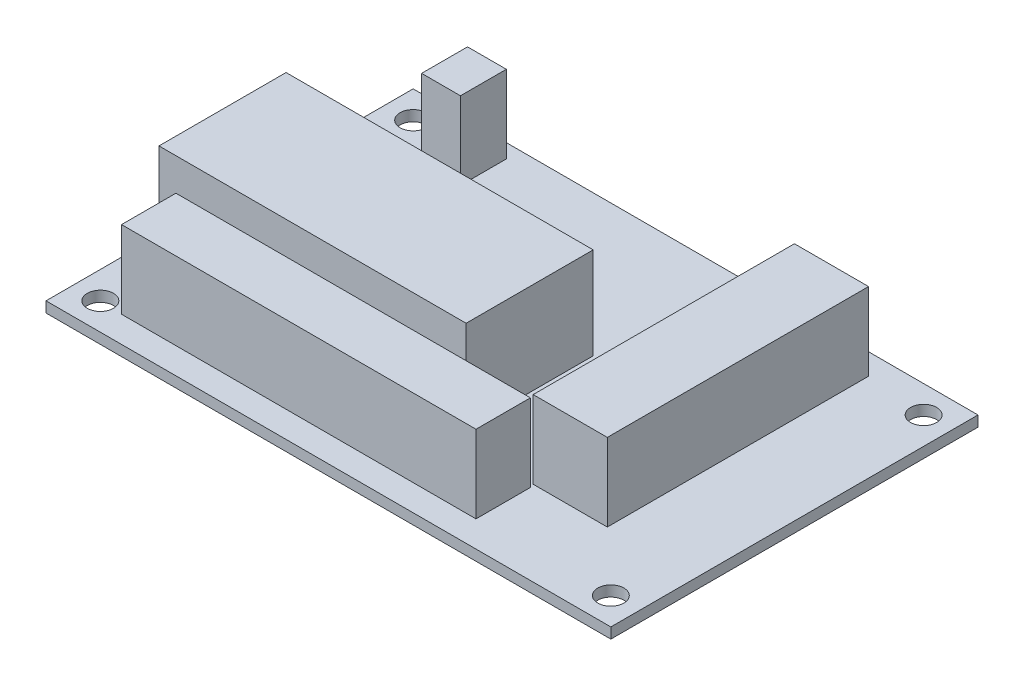
SolidWorks part; units mm, degrees
ref_plane "Front Plane" through (0, 0, 0) normal (0, 0, 1) x (1, 0, 0)
ref_plane "Top Plane" through (0, 0, 0) normal (0, 1, 0) x (1, 0, 0)
ref_plane "Right Plane" through (0, 0, 0) normal (1, 0, 0) x (0, 0, -1)
sketch "Sketch1" plane through (0, 0, 0) normal (0, 1, 0) x (1, 0, 0)
  line L1 (0, 0) -> (80, 0)
  line L2 (0, 0) -> (0, 52)
  line L3 (0, 52) -> (80, 52)
  line L4 (80, 0) -> (80, 52)
  circle A0 centre (3.85, 48.15) radius 1.85
  circle A1 centre (3.85, 3.85) radius 1.85
  circle A2 centre (76.15, 48.15) radius 1.85
  circle A3 centre (76.15, 3.85) radius 1.85
  dimension "D3" = 3.7
  dimension "D4" = 3.7
  dimension "D5" = 3.7
  dimension "D6" = 3.7
  dimension "D7" = 3.85
  dimension "D8" = 3.85
  dimension "D9" = 3.85
  dimension "D10" = 3.85
  dimension "D11" = 3.85
  dimension "D12" = 3.85
  dimension "D13" = 3.85
  dimension "D14" = 3.85
  dimension "D1" = 52
  dimension "D2" = 80
extrude "Boss-Extrude1" add sketch "Sketch1" along normal blind 1.5
sketch "Sketch2" plane through (0, 1.5, 0) normal (0, 1, 0) x (1, 0, 0)
  line L0 (0, 52) -> (0, 0) construction
  line L1 (2, 32) -> (45.5, 32)
  line L2 (2, 32) -> (2, 14)
  line L3 (2, 14) -> (45.5, 14)
  line L4 (45.5, 32) -> (45.5, 14)
  line L5 (0, 0) -> (80, 0) construction
  dimension "D1" = 43.5
  dimension "D2" = 18
  dimension "D3" = 2
  dimension "D4" = 14
extrude "Boss-Extrude2" add sketch "Sketch2" along normal blind 13
sketch "Sketch3" plane through (0, 1.5, 0) normal (0, 1, 0) x (1, 0, 0)
  line L0 (80, 52) -> (0, 52) construction
  line L1 (57, 49) -> (67.5, 49)
  line L2 (57, 49) -> (57, 12)
  line L3 (57, 12) -> (67.5, 12)
  line L4 (67.5, 49) -> (67.5, 12)
  line L5 (80, 0) -> (80, 52) construction
  line L6 (0, 52) -> (0, 0) construction
  line L7 (7, 11.4) -> (57.2, 11.4)
  line L8 (7, 11.4) -> (7, 3.7)
  line L9 (7, 3.7) -> (57.2, 3.7)
  line L10 (57.2, 11.4) -> (57.2, 3.7)
  line L11 (0, 0) -> (80, 0) construction
  line L13 (9.7, 43.5) -> (15.2, 43.5)
  line L14 (9.7, 43.5) -> (9.7, 50)
  line L15 (9.7, 50) -> (15.2, 50)
  line L16 (15.2, 43.5) -> (15.2, 50)
  dimension "D1" = 10.5
  dimension "D2" = 37
  dimension "D3" = 3
  dimension "D4" = 12.5
  dimension "D5" = 7.7
  dimension "D6" = 50.2
  dimension "D7" = 7
  dimension "D8" = 3.7
  dimension "D9" = 5.5
  dimension "D10" = 6.5
  dimension "D11" = 2
  dimension "D12" = 9.7
extrude "Boss-Extrude3" add sketch "Sketch3" along normal blind 11
